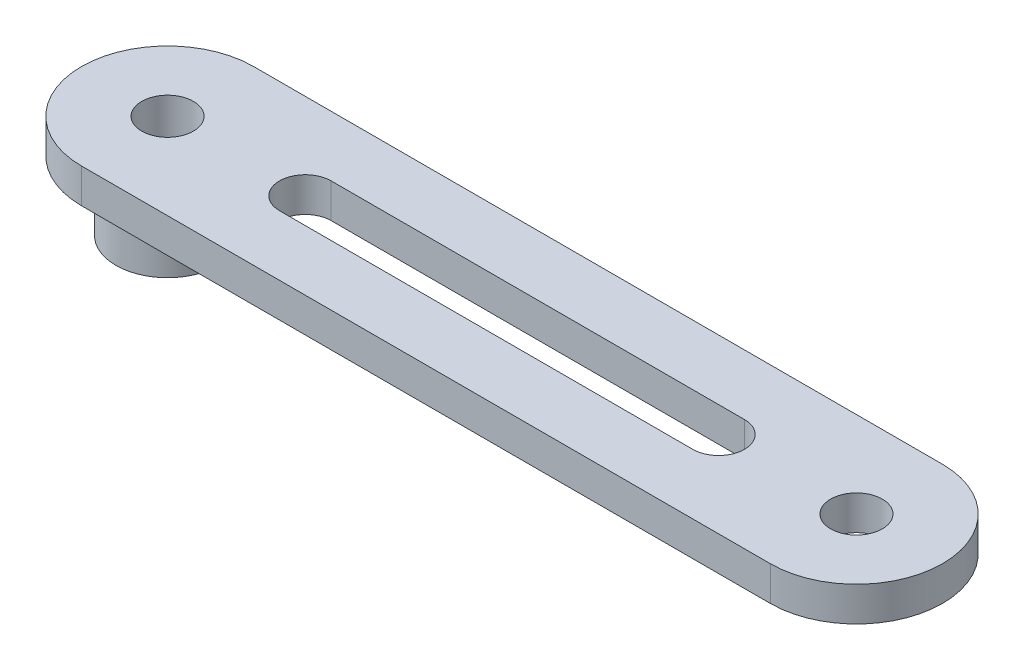
SolidWorks part; units mm, degrees
ref_plane "Front Plane" through (0, 0, 0) normal (0, 0, 1) x (1, 0, 0)
ref_plane "Top Plane" through (0, 0, 0) normal (0, 1, 0) x (1, 0, 0)
ref_plane "Right Plane" through (0, 0, 0) normal (1, 0, 0) x (0, 0, -1)
sketch "Sketch2" plane through (0, 0, 0) normal (0, 1, 0) x (1, 0, 0)
  line L0 (-60, 0) -> (60, 0) construction
  line L5 (-60, 7.5) -> (60, 7.5)
  line L6 (-60, -7.5) -> (60, -7.5)
  line L7 (-100, 0) -> (100, 0) construction
  line L8 (-100, 25) -> (100, 25)
  line L9 (-100, -25) -> (100, -25)
  arc A4 (-60, 7.5) -> (-60, -7.5) centre (-60, 0) ccw
  arc A5 (60, -7.5) -> (60, 7.5) centre (60, 0) ccw
  arc A6 (-100, 25) -> (-100, -25) centre (-100, 0) ccw
  arc A7 (100, -25) -> (100, 25) centre (100, 0) ccw
  circle A8 centre (100, 0) radius 7.5
  circle A9 centre (-100, 0) radius 7.5
  point P2 (0, 0)
  point P10 (0, 0)
  point P11 (0, 29.878)
  dimension "D3" = 50
  dimension "D5" = 15
  dimension "D2" = 200
  dimension "D1" = 15
  dimension "D4" = 120
extrude "Boss-Extrude1" add sketch "Sketch2" along normal blind 10
sketch "Sketch3" plane through (0, 0, 0) normal (0, -1, 0) x (1, 0, 0)
  circle A0 centre (-100, 0) radius 15
  circle A1 centre (-100, 0) radius 7.5
  dimension "D1" = 30
extrude "Boss-Extrude2" add sketch "Sketch3" along normal blind 20
